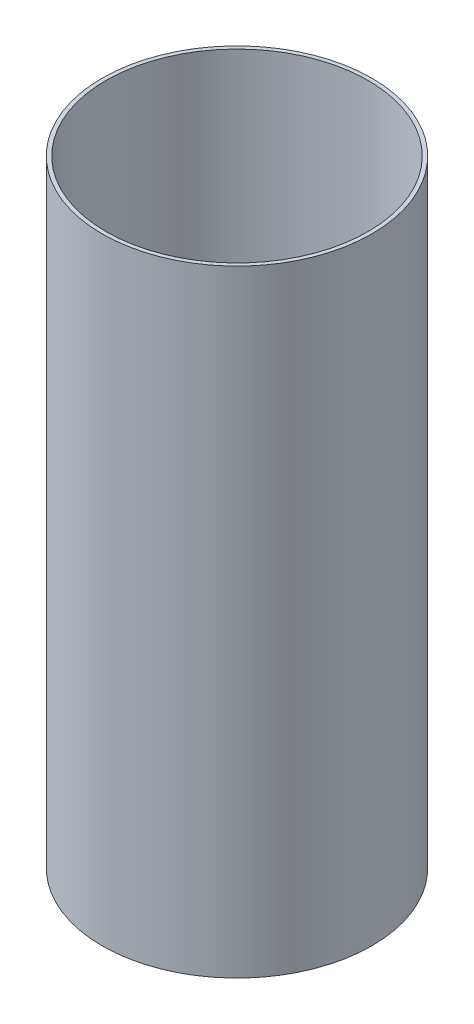
SolidWorks part; units mm, degrees
material "Fibra de Vidro A"
ref_plane "Plano frontal" through (0, 0, 0) normal (0, 0, 1) x (1, 0, 0)
ref_plane "Plano superior" through (0, 0, 0) normal (0, 1, 0) x (1, 0, 0)
ref_plane "Plano direito" through (0, 0, 0) normal (1, 0, 0) x (0, 0, -1)
sketch "Esboço1" plane through (0, 0, 0) normal (0, 1, 0) x (1, 0, 0)
  circle A0 centre (0, 0) radius 35
  circle A1 centre (0, 0) radius 34
  dimension "D1" = 70
  dimension "D2" = 68
extrude "Ressalto-extrusão1" add sketch "Esboço1" along normal blind 160
